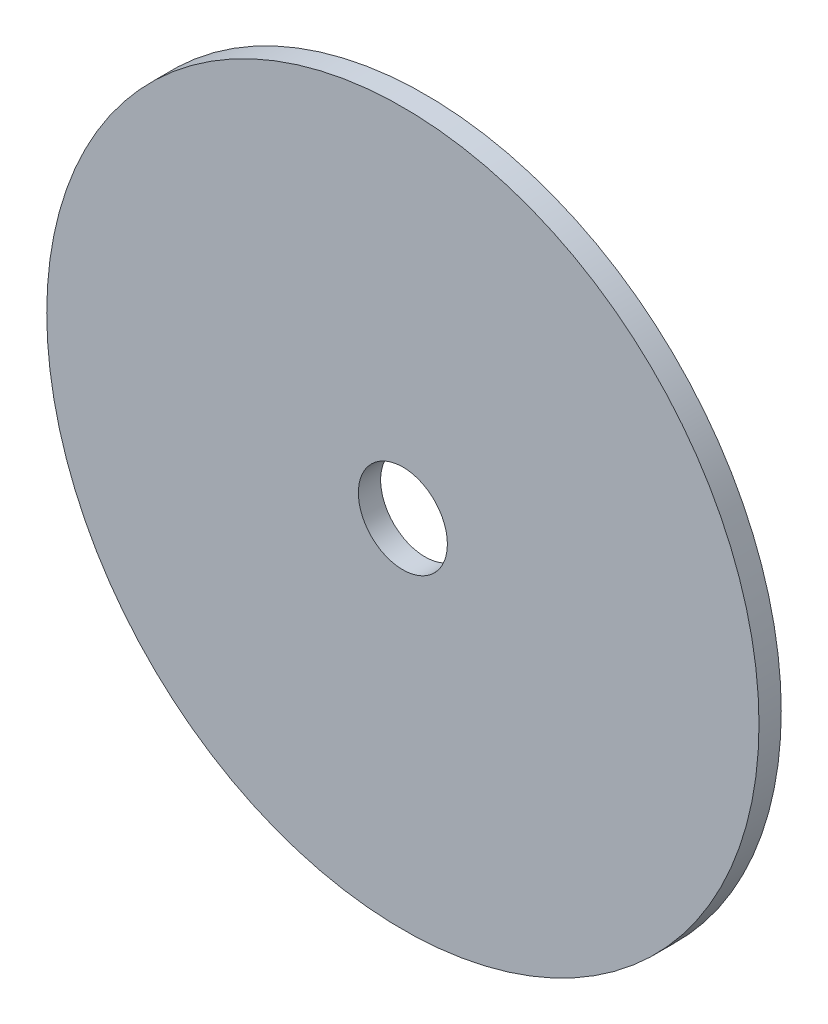
SolidWorks part; units mm, degrees
ref_plane "Front Plane" through (0, 0, 0) normal (0, 0, 1) x (1, 0, 0)
ref_plane "Top Plane" through (0, 0, 0) normal (0, 1, 0) x (1, 0, 0)
ref_plane "Right Plane" through (0, 0, 0) normal (1, 0, 0) x (0, 0, -1)
sketch "Sketch1" plane through (0, 0, 0) normal (0, 0, 1) x (1, 0, 0)
  circle A0 centre (0, 0) radius 50.8
  circle A1 centre (0, 0) radius 6.35
  dimension "D1" = 101.6
  dimension "D2" = 12.7
extrude "Boss-Extrude2" add sketch "Sketch1" along normal blind 3.175
